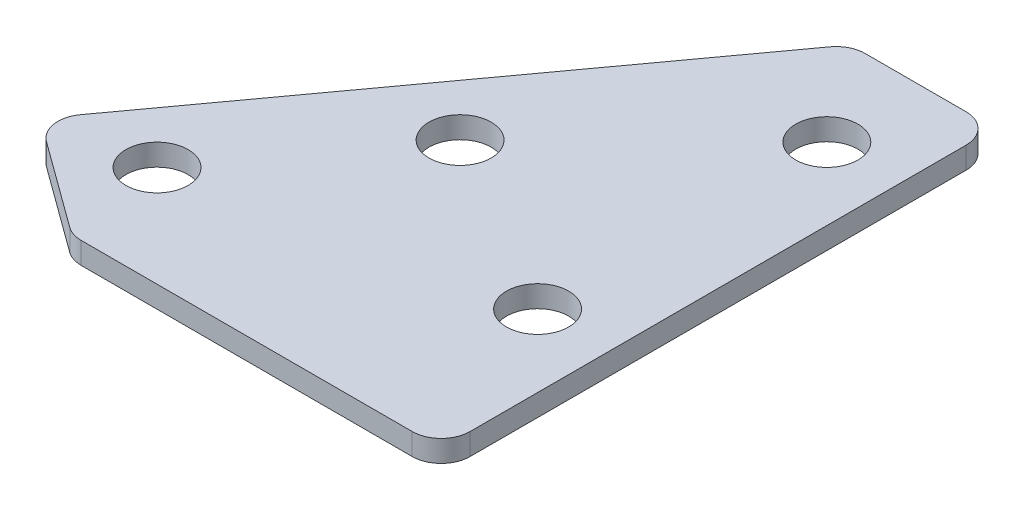
SolidWorks part; units mm, degrees
material "5052-H34"
ref_plane "正面" through (0, 0, 0) normal (0, 0, 1) x (1, 0, 0)
ref_plane "平面" through (0, 0, 0) normal (0, 1, 0) x (1, 0, 0)
ref_plane "右側面" through (0, 0, 0) normal (1, 0, 0) x (0, 0, -1)
sketch "ｽｹｯﾁ1" plane through (0, 0, 0) normal (0, 1, 0) x (1, 0, 0)
  line L0 (0, 0) -> (90196.146, 0) construction
  line L1 (189.5, 0) -> (189.5, 261.6288) construction
  line L2 (0, 0) -> (189.5, 260) construction
  line L3 (175.6053, 249.4249) -> (183.6866, 243.5349) construction
  line L4 (-6.9857, -1.0956) -> (1.0956, -6.9857) construction
  line L5 (94.75, 130) -> (98.7907, 127.055) construction
  line L6 (183.6866, 243.5349) -> (1.0956, -6.9857) construction
  line L7 (184.5, 0) -> (184.5, 261.6288) construction
  line L8 (168.9615, 223.3316) -> (160.8802, 229.2216)
  line L9 (184.5, 261.6288) -> (194.5, 261.6288)
  line L10 (194.5, 261.6288) -> (194.5, 223.3316)
  line L11 (194.5, 223.3316) -> (168.9615, 223.3316)
  line L13 (184.5, 261.6288) -> (160.8802, 229.2216)
  circle A0 centre (0, 0) radius 2.15 construction
  circle A1 centre (189.5, 260) radius 2.15 construction
  circle A2 centre (176.7009, 242.4392) radius 2.15
  circle A3 centre (189.5, 235) radius 2.15
  circle A4 centre (167.8659, 230.3173) radius 2.15
  circle A5 centre (189.5, 255) radius 2.15
  dimension "D1" = 189.5
  dimension "D2" = 4.3
  dimension "D3" = 260
  dimension "D5" = 5
  dimension "D7" = 5
  dimension "D8" = 5
  dimension "D9" = 25
  dimension "D11" = 20
  dimension "D12" = 15
  dimension "D14" = 5
  dimension "D4" = 10
  dimension "D6" = 310
  dimension "D10" = 5
  dimension "D13" = 10
extrude "ﾎﾞｽ - 押し出し1" add sketch "ｽｹｯﾁ1" along normal blind 1.5
fillet "ﾌｨﾚｯﾄ1" radius 2 5 edges at (168.9615, 0.75, -223.3316) (160.8802, 0.75, -229.2216) (194.5, 0.75, -223.3316) (194.5, 0.75, -261.6288) (184.5, 0.75, -261.6288)
